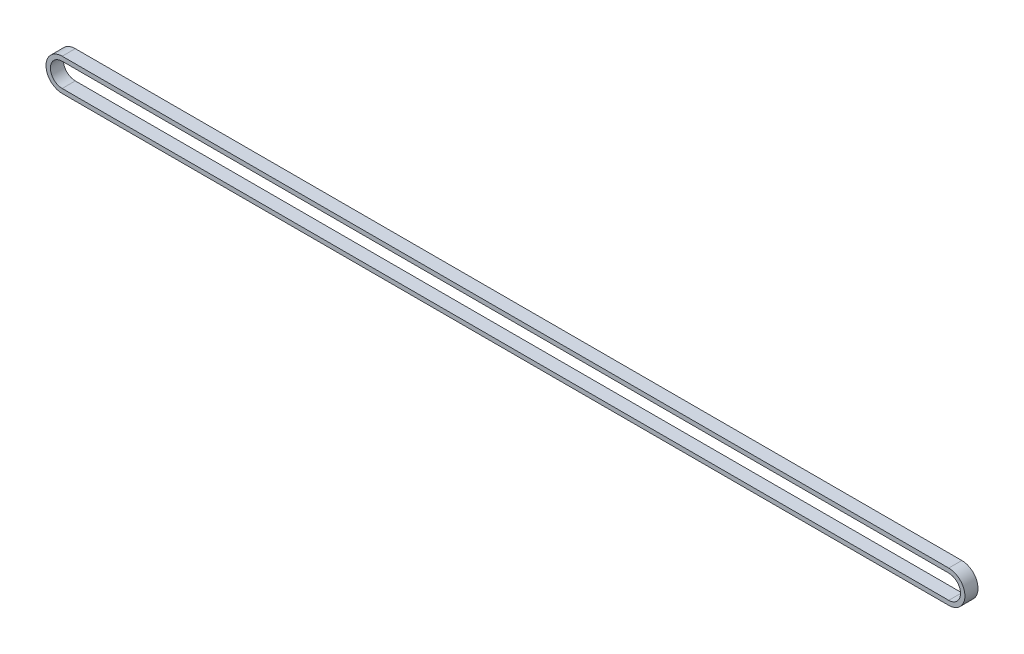
SolidWorks part; units mm, degrees
material "NBR"
ref_plane "Plano frontal" through (0, 0, 0) normal (0, 0, 1) x (1, 0, 0)
ref_plane "Plano superior" through (0, 0, 0) normal (0, 1, 0) x (1, 0, 0)
ref_plane "Plano direito" through (0, 0, 0) normal (1, 0, 0) x (0, 0, -1)
sketch "Esboço1" plane through (0, 0, 0) normal (0, 0, 1) x (1, 0, 0)
  line L0 (-203, 0) -> (0, 0) construction
  line L1 (0, 0) -> (0, 11.8238) construction
  line L2 (-203, 7.4) -> (203, 7.4)
  line L3 (-203, 5.4) -> (203, 5.4)
  line L4 (-203, -5.4) -> (203, -5.4)
  line L5 (-203, -7.4) -> (203, -7.4)
  circle A0 centre (-203, 0) radius 5.4
  circle A1 centre (-203, 0) radius 7.4
  circle A2 centre (203, 0) radius 7.4
  circle A3 centre (203, 0) radius 5.4
  point P20 (0, -7.4)
  point P21 (0, -5.4)
  point P22 (0, 5.4)
  point P23 (0, 7.4)
  dimension "D1" = 10.8
  dimension "D2" = 2
  dimension "D3" = 406
extrude "Ressalto-extrusão1" add sketch "Esboço1" along normal mid plane 6 contours L3 A2 L2 A1 | L3 A1 L4 A0 | L5 A2 L4 A1 | L3 A3 L4 A2
